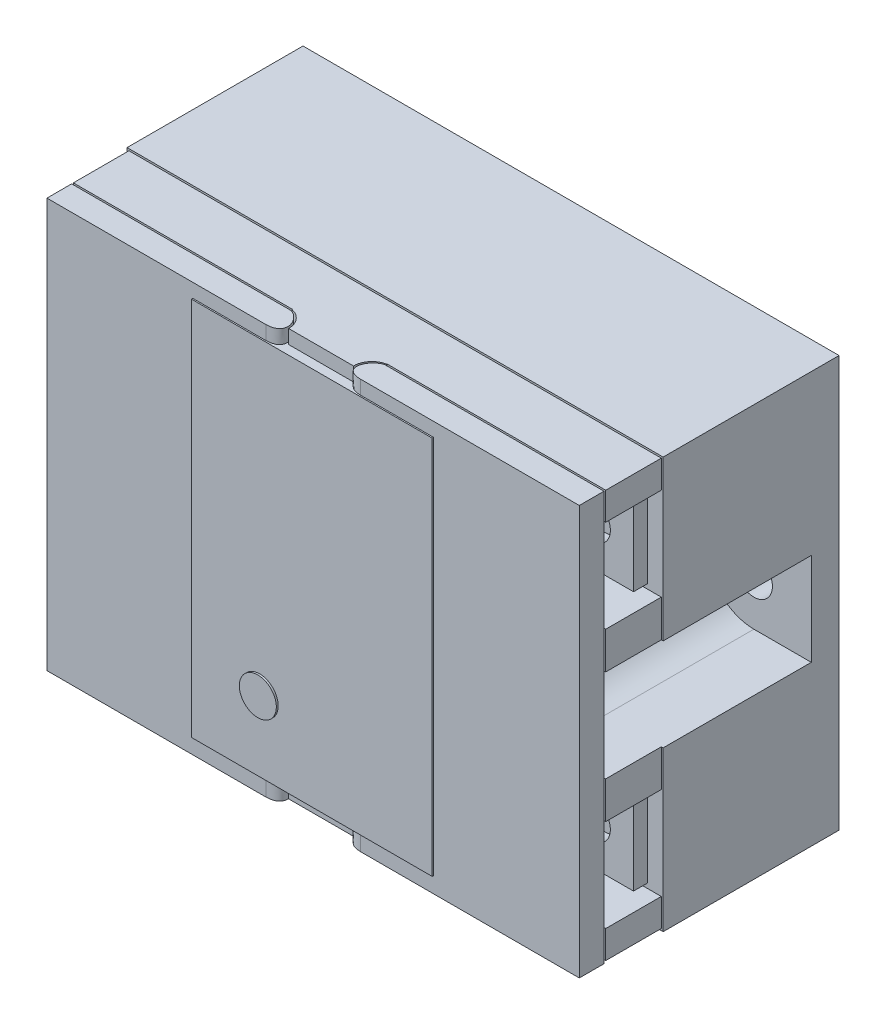
SolidWorks part; units mm, degrees
ref_plane "Front Plane" through (0, 0, 0) normal (0, 0, 1) x (1, 0, 0)
ref_plane "Top Plane" through (0, 0, 0) normal (0, 1, 0) x (1, 0, 0)
ref_plane "Right Plane" through (0, 0, 0) normal (1, 0, 0) x (0, 0, -1)
sketch "Sketch1" plane through (0, 0, 0) normal (0, 0, 1) x (1, 0, 0)
  line L1 (-28.75, 22) -> (28.75, 22)
  line L2 (-28.75, 22) -> (-28.75, -22)
  line L3 (-28.75, -22) -> (28.75, -22)
  line L4 (28.75, 22) -> (28.75, -22)
  line L5 (-28.75, 22) -> (28.75, -22) construction
  line L6 (-28.75, -22) -> (28.75, 22) construction
  point P0 (0, 0)
  dimension "D1" = 44
  dimension "D2" = 57.5
extrude "Boss-Extrude1" add sketch "Sketch1" along normal blind 28
sketch "Sketch2" plane through (0, 0, 28) normal (0, 0, 1) x (1, 0, 0)
  line L1 (-13.5, 20.5) -> (13.5, 20.5)
  line L2 (-13.5, 20.5) -> (-13.5, -20.5)
  line L3 (-13.5, -20.5) -> (13.5, -20.5)
  line L4 (13.5, 20.5) -> (13.5, -20.5)
  line L5 (-13.5, 20.5) -> (13.5, -20.5) construction
  line L6 (-13.5, -20.5) -> (13.5, 20.5) construction
  line L10 (28.75, -22) -> (28.75, 22)
  line L11 (28.75, 22) -> (-28.75, 22)
  line L12 (-28.75, 22) -> (-28.75, -22)
  line L13 (-28.75, -22) -> (28.75, -22)
  line L14 (28.75, -22) -> (28.75, 22)
  line L15 (28.75, 22) -> (-28.75, 22)
  line L16 (-28.75, 22) -> (-28.75, -22)
  line L17 (-28.75, -22) -> (28.75, -22)
  point P0 (0, 0)
  dimension "D1" = 41
  dimension "D2" = 27
  dimension "D3" = 0
extrude "Cut-Extrude1" cut sketch "Sketch2" against normal blind 3
sketch "Sketch3" plane through (0, 22, 0) normal (0, 1, 0) x (1, 0, 0)
  line L0 (13.5, -25) -> (-13.5, -25) construction
  line L3 (3.5, -26.9995) -> (-3.5, -26.9995)
  line L8 (5.1, -25) -> (5.1, -23.2692)
  line L9 (5.1, -23.2692) -> (-5.1, -23.2692)
  line L11 (-5.1, -25) -> (-5.1, -23.2692)
  line L12 (3.5, -26.9995) -> (5.5, -26.9995) construction
  line L13 (28.75, -25) -> (-28.75, -25) construction
  line L14 (5.1, -25) -> (5.1, -25.0399)
  line L15 (0, -15.95) -> (0, 15.95) construction
  line L16 (28.75, -25) -> (-28.75, -25)
  line L17 (-5.1, -25.0399) -> (-5.1, -25)
  arc A2 (3.5, -26.9995) -> (5.1, -25.0399) centre (5.5, -26.9995) cw
  arc A3 (-3.5, -26.9995) -> (-5.1, -25.0399) centre (-5.5, -26.9995) ccw
  point P10 (3.4571, -25)
  point P18 (0, -25)
  point P19 (0, -23.2692)
  point P20 (0, -26.9995)
  line M11 (-28.75, -25) -> (28.75, -25)
  dimension "D3" = 2
  dimension "D2" = 7
  dimension "D5" = 1.7308
extrude "Boss-Extrude2" add sketch "Sketch3" against normal through all contours A3 L3 A2 L14 L17 M11 | L11 L8 L9 M11
sketch "Sketch4" plane through (0, 20.5, 0) normal (0, 1, 0) x (1, 0, 0)
  line L1 (13.5, -28) -> (13, -28)
  line L2 (13.5, -28) -> (13.5, -27.5)
  line L3 (13.5, -27.5) -> (13, -27.5)
  line L4 (13, -28) -> (13, -27.5)
  line L5 (-13.5, -28) -> (-13, -28)
  line L6 (-13.5, -28) -> (-13.5, -27.5)
  line L7 (-13.5, -27.5) -> (-13, -27.5)
  line L8 (-13, -28) -> (-13, -27.5)
  dimension "D1" = 0.5
extrude "Cut-Extrude2" cut sketch "Sketch4" against normal through all
sketch "Sketch5" plane through (0, 0, 25) normal (0, 0, 1) x (1, 0, 0)
  line L0 (28.75, -22) -> (28.75, 22) construction
  line L1 (28.75, 19) -> (16.75, 19)
  line L2 (28.75, 19) -> (28.75, 9)
  line L3 (28.75, 9) -> (16.75, 9)
  line L4 (16.75, 19) -> (16.75, 9)
  line L6 (28.75, 5) -> (22.75, 5)
  line L7 (28.75, 5) -> (28.75, -5)
  line L8 (28.75, -5) -> (22.75, -5)
  line L9 (22.75, 5) -> (22.75, -5)
  line L10 (28.75, -9) -> (16.75, -9)
  line L11 (28.75, -9) -> (28.75, -19)
  line L12 (28.75, -19) -> (16.75, -19)
  line L13 (16.75, -9) -> (16.75, -19)
  line L17 (5.1, 20.5) -> (13.5, 20.5)
  line L21 (28.75, 22) -> (5.1, 22)
  line L24 (5.1, 20.5) -> (13.5, 20.5)
  line L25 (13.5, 20.5) -> (13.5, -20.5)
  line L26 (13.5, 20.5) -> (13.5, -20.5)
  line L27 (5.1, -22) -> (28.75, -22)
  line L28 (28.75, -22) -> (28.75, 22)
  line L29 (28.75, 22) -> (5.1, 22)
  line L35 (5.1, -22) -> (28.75, -22)
  line L36 (28.75, -22) -> (28.75, 22)
  line L37 (13.5, -20.5) -> (5.1, -20.5)
  line L38 (13.5, -20.5) -> (5.1, -20.5)
  line L39 (5.1, 22) -> (5.1, 20.5)
  line L43 (5.1, 22) -> (5.1, 20.5)
  line L45 (5.1, -20.5) -> (5.1, -22)
  line L46 (5.1, -20.5) -> (5.1, -22)
  circle A0 centre (22.75, 0) radius 5
  point P16 (28.75, 0)
  point P18 (28.75, 0)
  line M28 (28.75, -22) -> (28.75, 22)
  dimension "D2" = 3
  dimension "D3" = 10
  dimension "D4" = 10
  dimension "D5" = 10
  dimension "D6" = 3
  dimension "D7" = 12
  dimension "D8" = 12
  dimension "D9" = 6
  dimension "D1" = 0
extrude "Cut-Extrude3" cut sketch "Sketch5" against normal blind 6 contours L10 L13 L12 M28 | L1 L4 L3 M28
sketch "Sketch6" plane through (0, 0, 25) normal (0, 0, 1) x (1, 0, 0)
  line L0 (28.75, -5) -> (22.75, -5) construction
  line L2 (28.75, 5) -> (22.75, 5) construction
  line L3 (22.75, 5) -> (22.75, -5) construction
  line L4 (28.75, -5) -> (22.75, -5)
  line L6 (28.75, 5) -> (22.75, 5)
  line L7 (22.75, 5) -> (22.75, -5)
  line L8 (28.75, 5) -> (31.1896, 5)
  line L9 (31.1896, 5) -> (31.1896, -5)
  line L10 (31.1896, -5) -> (28.75, -5)
  line L11 (28.75, 19) -> (28.75, 22) construction
  circle A0 centre (22.75, 0) radius 5 construction
  circle A1 centre (22.75, 0) radius 5
  line M2 (28.75, -9) -> (28.75, 9)
  dimension "D1" = 2.4396
extrude "Cut-Extrude4" cut sketch "Sketch6" against normal blind 22 contours A1 L4 L6 M2 | L7 A1 | L7 A1
mirror "Mirror1" about plane through (0, 0, 0) normal (1, 0, 0) of "Cut-Extrude4", "Cut-Extrude3"
sketch "Sketch8" plane through (0, 0, 28) normal (0, 0, 1) x (1, 0, 0)
  line L0 (13, 20.5) -> (13, -20.5) construction
  line L1 (13, 20.5) -> (-13, 20.5) construction
  circle A0 centre (-5.6282, -12.8686) radius 2
  dimension "D1" = 4
  dimension "D2" = 18.6282
  dimension "D3" = 33.3686
extrude "Boss-Extrude3" add sketch "Sketch8" along normal blind 0.2
sketch "Sketch9" plane through (0, 0, 0) normal (0, 0, -1) x (-1, 0, 0)
  line L0 (-27.75, 21) -> (-27.75, -21)
  line L1 (-27.75, -21) -> (27.75, -21)
  line L2 (27.75, -21) -> (27.75, 21)
  line L3 (27.75, 21) -> (-27.75, 21)
  line L4 (-28.75, 22) -> (-28.75, -22)
  line L6 (-28.75, 22) -> (-28.75, -22)
  line L16 (-28.75, -22) -> (28.75, -22)
  line L18 (-28.75, -22) -> (28.75, -22)
  line L20 (28.75, -22) -> (28.75, 22)
  line L21 (28.75, -22) -> (28.75, 22)
  line L22 (28.75, 22) -> (-28.75, 22)
  line L23 (28.75, 22) -> (-28.75, 22)
  dimension "D1" = 0
extrude "Boss-Extrude4" add sketch "Sketch9" along normal blind 0.2 contours L0 L1 L2 L3
sketch "Sketch7" plane through (0, 0, 3) normal (0, 0, 1) x (1, 0, 0)
  circle A0 centre (22.75, 0) radius 2
  circle A1 centre (-22.75, 0) radius 2
  dimension "D1" = 4
  dimension "D2" = 4
extrude "Cut-Extrude5" cut sketch "Sketch7" against normal blind 22
sketch "Sketch10" plane through (0, 0, 0) normal (0, 0, -1) x (-1, 0, 0)
  line L0 (-28.95, 22.2) -> (-28.95, -22.2)
  line L1 (-28.95, -22.2) -> (28.95, -22.2)
  line L2 (28.95, -22.2) -> (28.95, 22.2)
  line L3 (28.95, 22.2) -> (-28.95, 22.2)
  line L4 (-28.75, 22) -> (-28.75, -22)
  line L5 (-28.75, -22) -> (28.75, -22)
  line L6 (28.75, -22) -> (28.75, 22)
  line L7 (28.75, 22) -> (-28.75, 22)
  line L8 (-28.75, 22) -> (-28.75, -22)
  line L9 (-28.75, -22) -> (28.75, -22)
  line L10 (28.75, -22) -> (28.75, 22)
  line L11 (28.75, 22) -> (-28.75, 22)
  dimension "D1" = 0
  dimension "D2" = 0.2
extrude "Boss-Extrude5" add sketch "Sketch10" against normal blind 19
sketch "Sketch11" plane through (0, 0, 25) normal (0, 0, 1) x (1, 0, 0)
  line L0 (-28.75, 5) -> (-31.3343, 5)
  line L1 (-31.3343, 5) -> (-31.3343, -5)
  line L2 (-31.3343, -5) -> (-28.75, -5)
  line L3 (-22.75, 5) -> (-28.75, 5)
  line L4 (-28.75, 5) -> (-28.75, -5)
  line L5 (-28.75, -5) -> (-22.75, -5)
  line L6 (-22.75, 5) -> (-28.75, 5)
  line L7 (-28.75, 5) -> (-28.75, -5)
  line L8 (-28.75, -5) -> (-22.75, -5)
  line L9 (28.75, 5) -> (22.75, 5)
  line L10 (22.75, -5) -> (28.75, -5)
  line L11 (28.75, -5) -> (28.75, 5)
  line L12 (28.75, 5) -> (22.75, 5)
  line L13 (22.75, -5) -> (28.75, -5)
  line L14 (28.75, -5) -> (28.75, 5)
  line L15 (28.75, 5) -> (30.3991, 5)
  line L16 (30.3991, 5) -> (30.3991, -5)
  line L17 (30.3991, -5) -> (28.75, -5)
  line L18 (-28.75, -19) -> (-28.75, -22) construction
  arc A1 (-22.75, -5) -> (-22.75, 5) centre (-22.75, 0) ccw
  arc A2 (-22.75, -5) -> (-22.75, 5) centre (-22.75, 0) ccw
  arc A3 (22.75, 5) -> (22.75, -5) centre (22.75, 0) ccw
  arc A4 (22.75, 5) -> (22.75, -5) centre (22.75, 0) ccw
  dimension "D3" = 59.1491
  dimension "D4" = 2.5843
  dimension "D1" = 0
  dimension "D2" = 0
extrude "Cut-Extrude6" cut sketch "Sketch11" against normal blind 22 contours L7 L0 L1 L2 | L17 L16 L15 L14
sketch "Sketch12" plane through (0, 0, 19) normal (0, 0, 1) x (1, 0, 0)
  line L0 (-22.75, -9) -> (-22.75, -19) construction
  line L1 (-28.75, -9) -> (-16.75, -9) construction
  line L2 (-28.75, -19) -> (-16.75, -19) construction
  line L4 (-27.25, -9.5) -> (-18.25, -9.5)
  line L5 (-27.25, -9.5) -> (-27.25, -18.5)
  line L6 (-27.25, -18.5) -> (-18.25, -18.5)
  line L7 (-18.25, -9.5) -> (-18.25, -18.5)
  line L8 (-27.25, -9.5) -> (-18.25, -18.5) construction
  line L9 (-27.25, -18.5) -> (-18.25, -9.5) construction
  circle A0 centre (-22.75, -14) radius 2
  point P6 (-22.75, -14)
  dimension "D4" = 4
  dimension "D1" = 0.5
  dimension "D2" = 9
  dimension "D3" = 9
extrude "Boss-Extrude6" add sketch "Sketch12" along normal blind 1.5
mirror "Mirror2" about plane through (0, 0, 0) normal (0, 1, 0) of "Boss-Extrude6"
mirror "Mirror3" about plane through (0, 0, 0) normal (1, 0, 0) of "Mirror2", "Boss-Extrude6"
ref_plane "Plane1" through (0, 0, 0) normal (0, 1, 0) x (1, 0, 0)
sketch "Sketch14" plane through (0, 22, 0) normal (0, 1, 0) x (1, 0, 0)
  line L0 (-5.1, -25.187) -> (-28.75, -25.187)
  line L1 (-28.75, -25.187) -> (-28.75, -27.8555)
  line L2 (-28.75, -27.8555) -> (-5.1, -27.8555)
  line L4 (-28.75, -25) -> (-28.75, -19) construction
  line L6 (0, -15.62) -> (0, 15.62) construction
  line L7 (28.75, -27.8555) -> (5.1, -27.8555)
  line L8 (28.75, -25.187) -> (28.75, -27.8555)
  line L9 (5.1, -25.187) -> (28.75, -25.187)
  line L13 (-28.75, -19) -> (28.75, -19) construction
  spline S0 degree 3 poles (-5.1, -27.8555) (-4.3092, -27.8372) (-3.7987, -27.4933) (-3.6205, -26.2988) (-4.3999, -25.3311) (-5.1, -25.187) knots 0 0 0 0 0.351045 0.451045 1 1 1 1
  spline S1 degree 3 poles (5.1, -27.8555) (4.3092, -27.8372) (3.7987, -27.4933) (3.6205, -26.2988) (4.3999, -25.3311) (5.1, -25.187) knots 0 0 0 0 0.351045 0.451045 1 1 1 1
  dimension "D1" = 23.65
  dimension "D2" = 25.0108
  dimension "D3" = 6.187
  dimension "D4" = 8.0512
  dimension "D5" = 8.8555
extrude "Boss-Extrude7" add sketch "Sketch14" against normal through all separate body
